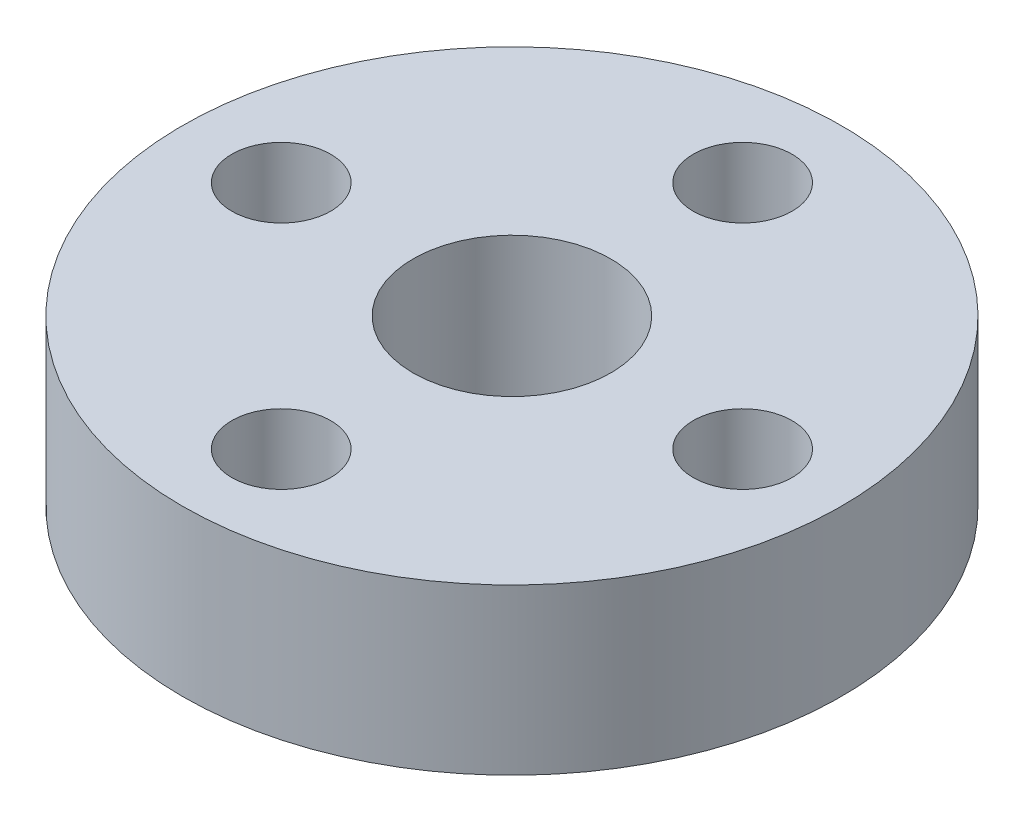
SolidWorks part; units mm, degrees
ref_plane "Спереди" through (0, 0, 0) normal (0, 0, 1) x (1, 0, 0)
ref_plane "Сверху" through (0, 0, 0) normal (0, 1, 0) x (1, 0, 0)
ref_plane "Справа" through (0, 0, 0) normal (1, 0, 0) x (0, 0, -1)
sketch "Эскиз1" plane through (0, 0, 0) normal (0, 1, 0) x (1, 0, 0)
  circle A0 centre (0, 0) radius 10
  circle A1 centre (-7, 0) radius 1.5
  circle A5 centre (0, 7) radius 1.5
  circle A6 centre (7, 0) radius 1.5
  circle A7 centre (0, -7) radius 1.5
  circle A8 centre (0, 0) radius 3
  point P14 (0, 0)
  dimension "D1" = 20
  dimension "D2" = 3
  dimension "D5" = 6
  dimension "D3" = 7
  dimension "D4" = 4
extrude "Бобышка-Вытянуть1" add sketch "Эскиз1" along normal blind 5
